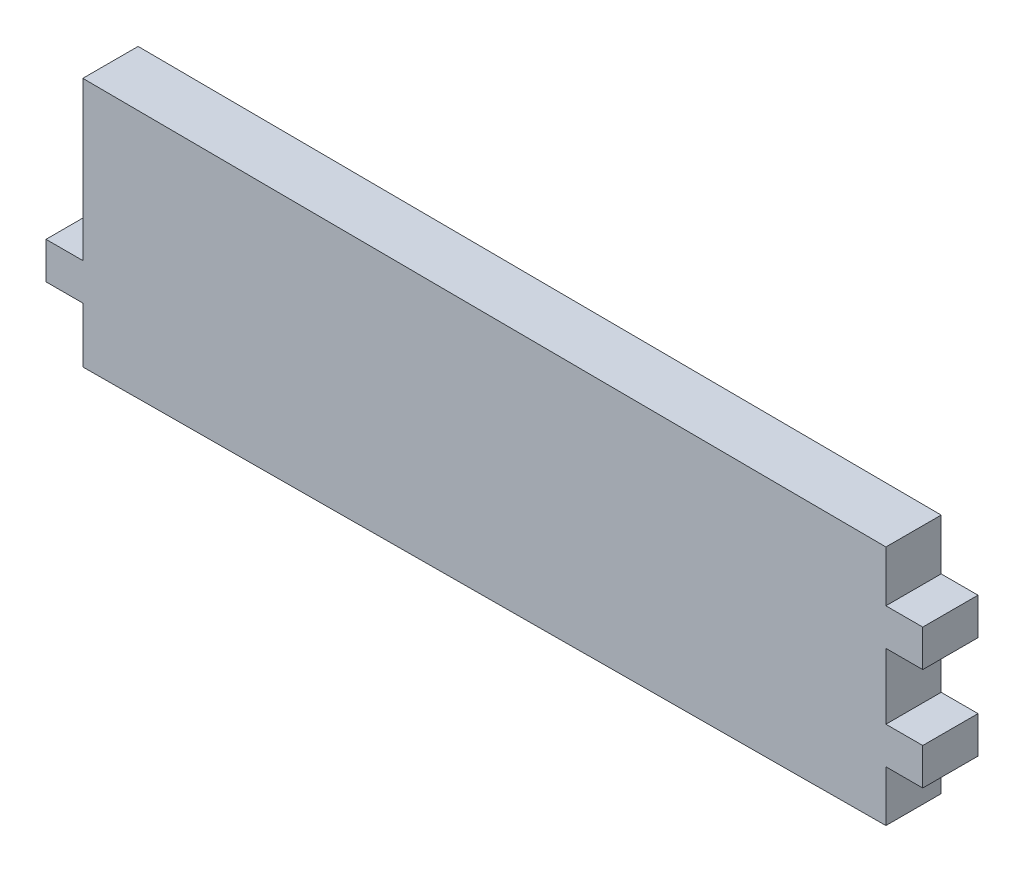
SolidWorks part; units mm, degrees
material "Balsa"
ref_plane "Front Plane" through (0, 0, 0) normal (0, 0, 1) x (1, 0, 0)
ref_plane "Top Plane" through (0, 0, 0) normal (0, 1, 0) x (1, 0, 0)
ref_plane "Right Plane" through (0, 0, 0) normal (1, 0, 0) x (0, 0, -1)
sketch "Sketch1" plane through (0, 0, 0) normal (0, 0, 1) x (1, 0, 0)
  line L0 (129.1138, -23.2864) -> (132.2888, -23.2864)
  line L1 (132.2888, -23.2864) -> (132.2888, -9.6814)
  line L2 (129.1138, -23.2864) -> (129.1138, -26.4614)
  line L3 (129.1138, -26.4614) -> (132.2888, -26.4614)
  line L4 (132.2888, -26.4614) -> (132.2888, -31.2272)
  line L5 (201.5038, -26.4614) -> (204.6788, -26.4614)
  line L6 (204.6788, -26.4614) -> (204.6788, -23.2864)
  line L7 (204.6788, -23.2864) -> (201.5038, -23.2864)
  line L8 (201.5038, -23.2864) -> (201.5038, -17.6222)
  line L9 (201.5038, -17.6222) -> (204.6788, -17.6222)
  line L10 (204.6788, -17.6222) -> (204.6788, -14.4472)
  line L11 (204.6788, -14.4472) -> (201.5038, -14.4472)
  line L12 (201.5038, -14.4472) -> (201.5038, -10.0552)
  line L13 (201.5038, -10.0552) -> (132.2888, -9.6814)
  line L14 (201.5038, -26.4614) -> (201.5038, -30.8535)
  line L15 (201.5038, -30.8535) -> (132.2888, -31.2272)
extrude "Boss-Extrude1" add sketch "Sketch1" along normal up to surface (4.7625 mm away)
